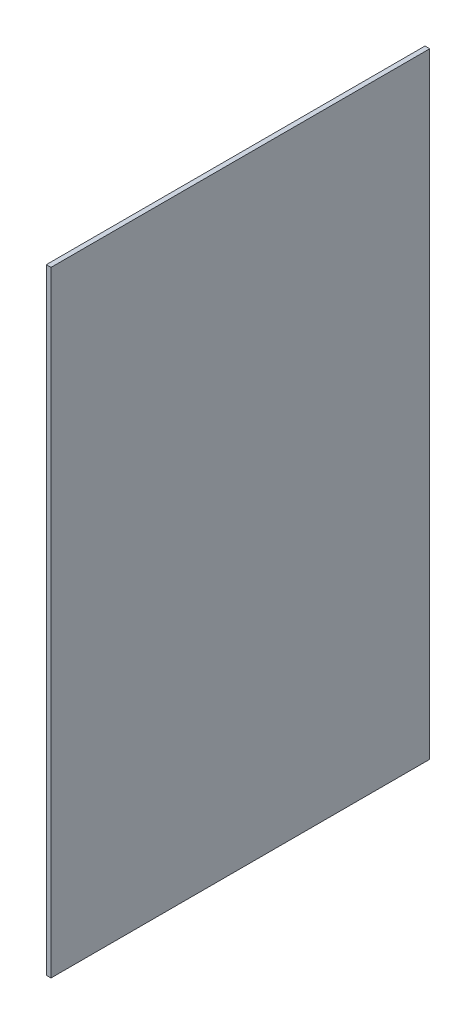
SolidWorks part; units mm, degrees
ref_plane "前视基准面" through (0, 0, 0) normal (0, 0, 1) x (1, 0, 0)
ref_plane "上视基准面" through (0, 0, 0) normal (0, 1, 0) x (1, 0, 0)
ref_plane "右视基准面" through (0, 0, 0) normal (1, 0, 0) x (0, 0, -1)
other "Configuration Table"
sketch "草图1" plane through (0, 0, 0) normal (0, 0, 1) x (1, 0, 0)
  line L0 (0, 0) -> (5, 0)
  line L1 (5, 0) -> (5, 650)
  line L2 (5, 650) -> (0, 650)
  line L3 (0, 650) -> (0, 0)
  dimension "width" = 5
  dimension "height" = 650
extrude "Continuous_leg_mounting_plate" add sketch "草图1" along normal blind 400
